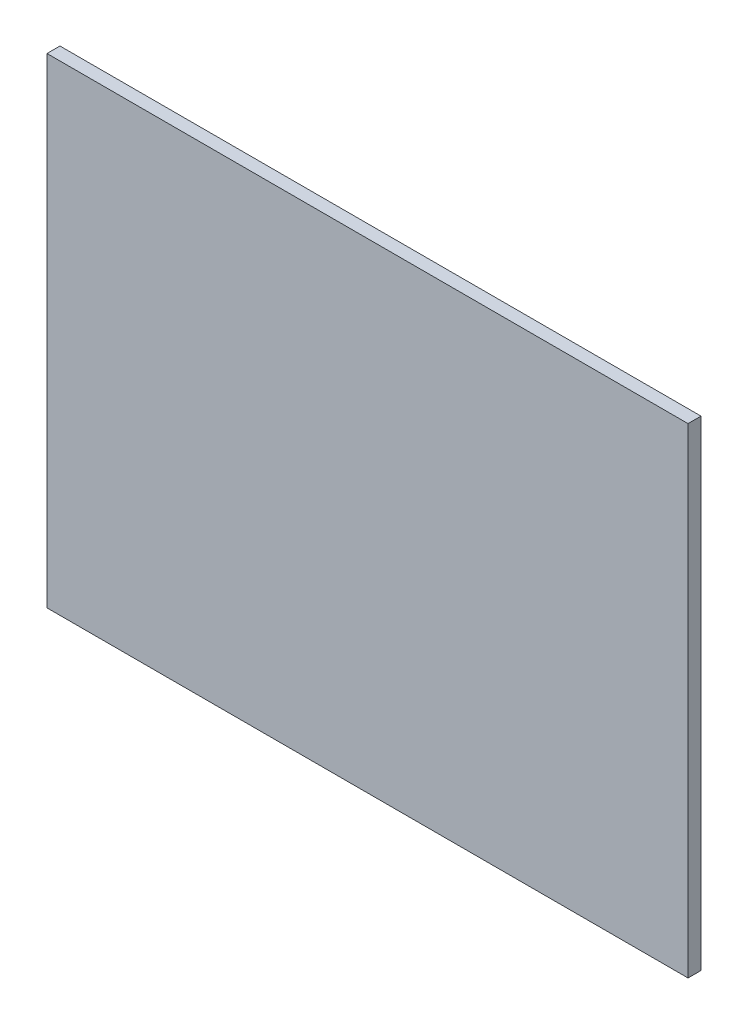
SolidWorks part; units mm, degrees
material "ABS PC"
ref_plane "Plan de face" through (0, 0, 0) normal (0, 0, 1) x (1, 0, 0)
ref_plane "Plan de dessus" through (0, 0, 0) normal (0, 1, 0) x (1, 0, 0)
ref_plane "Plan de droite" through (0, 0, 0) normal (1, 0, 0) x (0, 0, -1)
sketch "Esquisse1" plane through (0, 0, 0) normal (0, 0, 1) x (1, 0, 0)
  line L0 (123.5, 0) -> (-123.5, 0)
  line L1 (-123.5, 0) -> (-123.5, -185)
  line L2 (123.5, 0) -> (-123.5, 0) construction
  line L3 (-123.5, -185) -> (123.5, -185)
  line L5 (123.5, -185) -> (123.5, 0)
  line L7 (123.5, -8) -> (123.5, -308) construction
  line L8 (-123.5, -8) -> (-123.5, -308) construction
extrude "Boss.-Extru.1" add sketch "Esquisse1" against normal blind 5
